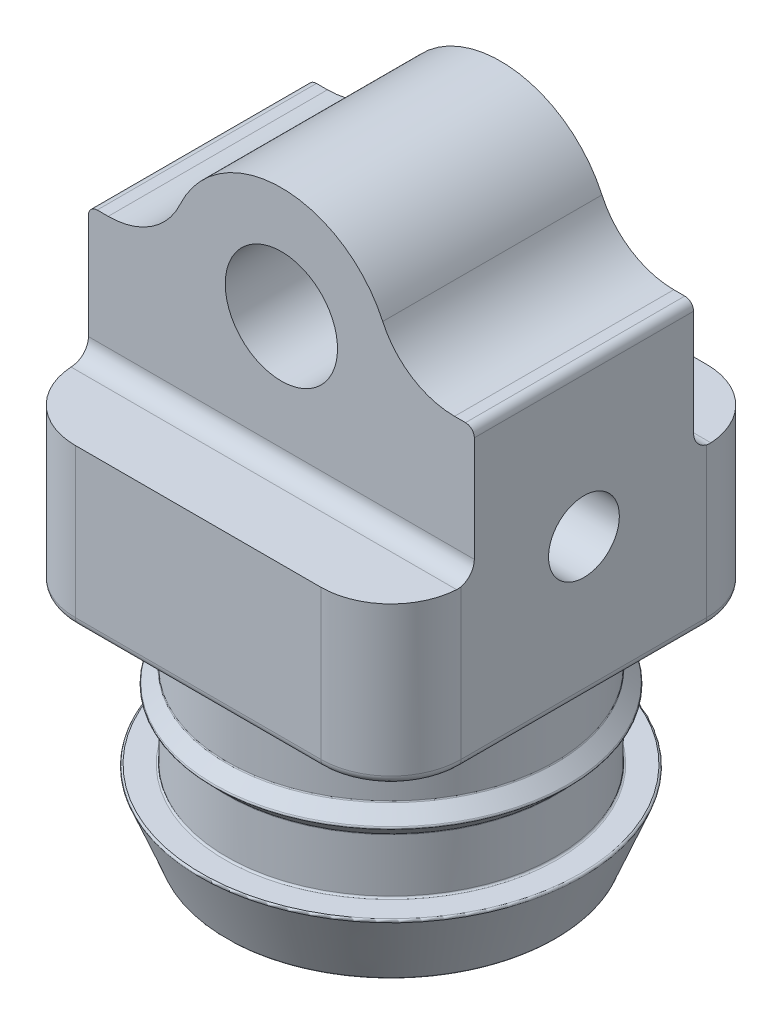
SolidWorks part; units mm, degrees
ref_plane "Front Plane" through (0, 0, 0) normal (0, 0, 1) x (1, 0, 0)
ref_plane "Top Plane" through (0, 0, 0) normal (0, 1, 0) x (1, 0, 0)
ref_plane "Right Plane" through (0, 0, 0) normal (1, 0, 0) x (0, 0, -1)
sketch "Sketch1" plane through (0, 0, 0) normal (0, 0, 1) x (1, 0, 0)
  line L3 (0, 0) -> (0, -16.5) construction
  line L4 (-11, 0) -> (-6.35, 0)
  line L5 (-11, 0) -> (-11, -16.5)
  line L6 (-11, -16.5) -> (11, -16.5)
  line L7 (11, 0) -> (11, -16.5)
  line L8 (6.35, 0) -> (11, 0)
  circle A0 centre (0, 0) radius 3.2
  arc A1 (6.35, 0) -> (-6.35, 0) centre (0, 0) ccw
  dimension "D1" = 6.4
  dimension "D2" = 12.7
  dimension "D4" = 22
  dimension "D5" = 16.5
extrude "Boss-Extrude1" add sketch "Sketch1" along normal mid plane 22
sketch3d "3DSketch1" plane through (0, 0, 0) normal (0, 0, 1) x (1, 0, 0)
  dimension "D1" = 12.7
sketch "Sketch2" plane through (0, 0, 0) normal (0, 0, 1) x (1, 0, 0)
  line L0 (0, 9.544) -> (0, -9.544) construction
  line L1 (0, -16.5) -> (9.365, -16.5)
  line L4 (0, -29.2) -> (9.365, -29.2)
  line L10 (0, -29.2) -> (0, -16.5)
  line L11 (9.365, -29.2) -> (10.9525, -25.2312)
  line L12 (10.9525, -25.2312) -> (9.365, -25.2312)
  line L13 (9.365, -25.2312) -> (9.365, -22.0563)
  line L14 (9.365, -22.0563) -> (10.1588, -21.2625)
  line L15 (10.1588, -21.2625) -> (9.365, -20.4688)
  line L16 (10.1588, -21.2625) -> (9.365, -21.2625) construction
  line L17 (9.365, -20.4688) -> (9.365, -16.5)
  dimension "D1" = 18.73
  dimension "D2" = 12.7
  dimension "D3" = 1.5875
  dimension "D4" = 3.9688
  dimension "D5" = 0.7937
  dimension "D6" = 7.9375
  dimension "D7" = 16.5
revolve "Revolve1" add sketch "Sketch2" angle 360 about L0
sketch "Sketch3" plane through (0, -29.2, 0) normal (0, -1, 0) x (1, 0, 0)
  circle A0 centre (0, 0) radius 4
  dimension "D1" = 8
extrude "Cut-Extrude1" cut sketch "Sketch3" against normal blind 20.5 contours A0
hole_wizard "#10-32 Tapped Hole1" positions "Sketch4" profile "Sketch5" tap size "#10-32" standard "ANSI Inch"
sketch "Sketch4" plane through (11, 0, 0) normal (1, 0, 0) x (0, 0, -1)
  point P0 (0, -8.5)
  dimension "D1" = 8.5
cosmetic thread "Hole Thread1" parameters "D1"=3.05, "D2"=4.826
sketch "Sketch5" plane through (11, -8.5, 0) normal (0, 1, 0) x (0, 0, -1)
  line L0 (0, 0) -> (0, 16.6433)
  line L1 (0, 16.6433) -> (2.0193, 15.43)
  line L2 (2.0193, 15.43) -> (2.0193, 0)
  line L5 (2.0193, 0) -> (0, 0)
  line L10 (0, 16.6433) -> (-2.0193, 15.43) construction
  line L11 (0, -6.35) -> (0, 107.95) construction
  dimension "Tap Drill Dia." = 4.0386
  dimension "Tap Drill Depth" = 15.43
  dimension "Drill Angle" = 118
fillet "Fillet3" radius 0.1 7 edges at (-10.9525, -25.2312, 0) (-10.1587, -21.2625, 0) (-9.365, -29.2, 0) (-9.365, -16.5, 0) (-9.365, -20.4688, 0) (-9.365, -22.0563, 0) (-9.365, -25.2312, 0)
fillet "Fillet7" radius 4.5 2 edges at (-6.35, 0, 0) (6.35, 0, 0)
fillet "Fillet6" radius 4 4 edges at (11, -8.25, -11) (-11, -8.25, -11) (-11, -8.25, 11) (11, -8.25, 11)
fillet "Fillet8" radius 0.5 24 edges at (-9.8284, -16.5, 9.8284) (-11, -16.5, 0) (-9.8284, -16.5, -9.8284) (0, -16.5, -11) (9.8284, -16.5, -9.8284) (11, -16.5, 0) (9.8284, -16.5, 9.8284) (10.7075, 0, 8.5015) (8.9278, 0.1004, 10.5048) (6.2987, 1.7659, 11) (0, 6.35, 11) (-6.2987, 1.7659, 11) (-8.0042, 0.4063, 10.8719) (-10.7075, 0, 8.5015) (-11, 0, 0) (-10.7075, 0, -8.5015) (-8.9278, 0.1004, -10.5048) (-6.2987, 1.7659, -11) (0, 6.35, -11) (6.2987, 1.7659, -11) (8.0042, 0.4063, -10.8719) (10.7075, 0, -8.5015) (0, -16.5, 11) (11, 0, 0)
sketch "Sketch7" plane through (11, 0, 0) normal (1, 0, 0) x (0, 0, -1)
  line L0 (0, 9.7903) -> (0, -13.5) construction
  line L1 (0, 0) -> (0, -16.5) construction
  line L2 (-12.0713, 6.6048) -> (-12.0713, -7.5)
  line L3 (-12.0713, -7.5) -> (-6.25, -7.5)
  line L4 (-6.25, -7.5) -> (-6.25, 6.6048)
  line L5 (-6.25, 6.6048) -> (-12.0713, 6.6048)
  line L7 (12.0713, -7.5) -> (6.25, -7.5)
  line L8 (6.25, -7.5) -> (6.25, 6.6048)
  line L9 (12.0713, 6.6048) -> (12.0713, -7.5)
  line L10 (6.25, 6.6048) -> (12.0713, 6.6048)
  dimension "D1" = 7.5
  dimension "D2" = 12.5
extrude "Cut-Extrude3" cut sketch "Sketch7" against normal through all
sketch "Sketch9" plane through (11, 0, 0) normal (1, 0, 0) x (0, 0, -1)
  line L0 (-6.25, -4) -> (6.25, -4)
  line L1 (-6.25, -7.5) -> (-6.25, -0.5) construction
  line L2 (6.25, -0.5) -> (6.25, -7.5) construction
fillet "Fillet9" radius 1 2 edges at (0, -7.5, -6.25) (0, -7.5, 6.25)
